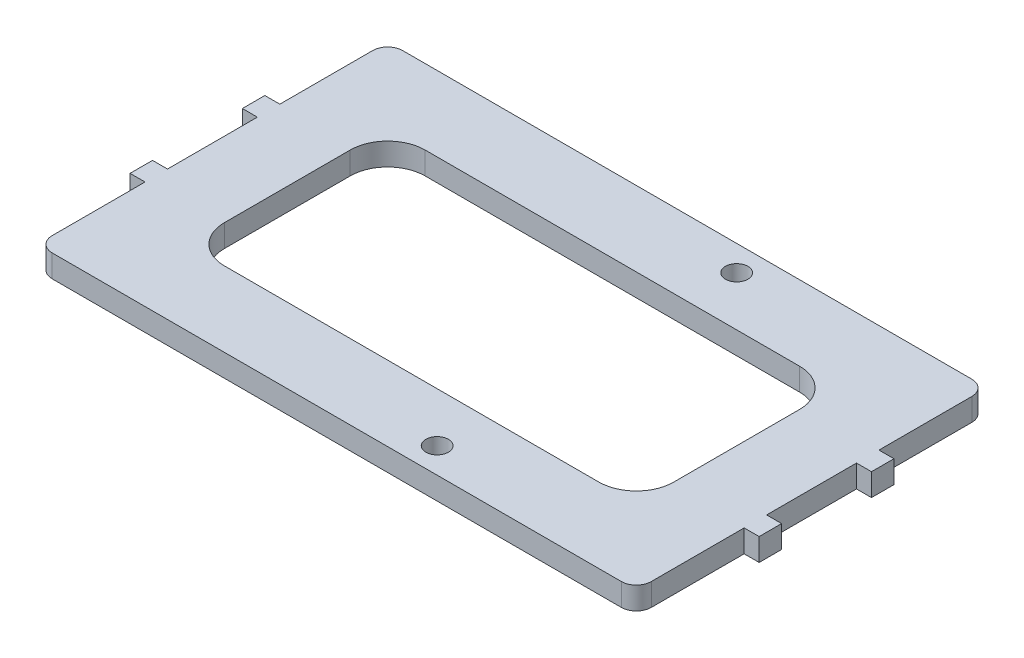
SolidWorks part; units mm, degrees
material "Copper"
ref_plane "Front Plane" through (0, 0, 0) normal (0, 0, 1) x (1, 0, 0)
ref_plane "Top Plane" through (0, 0, 0) normal (0, 1, 0) x (1, 0, 0)
ref_plane "Right Plane" through (0, 0, 0) normal (1, 0, 0) x (0, 0, -1)
sketch "Sketch1" plane through (0, 0, 0) normal (0, 1, 0) x (1, 0, 0)
  line L1 (0, 0) -> (101.6, 0)
  line L2 (0, 0) -> (0, 59.436)
  line L3 (0, 59.436) -> (101.6, 59.436)
  line L4 (101.6, 0) -> (101.6, 59.436)
  dimension "D1" = 59.436
  dimension "D2" = 101.6
extrude "Base Extrude" add sketch "Sketch1" along normal blind 3.81
fillet "Base Corner Fillet" radius 2.54 4 edges at (0, 1.905, 0) (0, 1.905, -59.436) (101.6, 1.905, -59.436) (101.6, 1.905, 0)
sketch "Sketch3" plane through (0, 0, 0) normal (-1, 0, 0) x (0, 0, 1)
  line L0 (-29.718, 3.81) -> (-29.718, 0) construction
  line L1 (-56.896, 3.81) -> (-2.54, 3.81) construction
  line L2 (-56.896, 0) -> (-2.54, 0) construction
  line L3 (-18.288, 3.81) -> (-22.098, 0) construction
  line L4 (-18.288, 0) -> (-22.098, 3.81) construction
  line L5 (-22.098, 0) -> (-22.098, 3.81)
  line L6 (-18.288, 3.81) -> (-22.098, 3.81)
  line L7 (-41.148, 0) -> (-37.338, 0)
  line L8 (-41.148, 0) -> (-41.148, 3.81)
  line L9 (-41.148, 3.81) -> (-37.338, 3.81)
  line L10 (-37.338, 0) -> (-37.338, 3.81)
  line L11 (-41.148, 0) -> (-37.338, 3.81) construction
  line L12 (-41.148, 3.81) -> (-37.338, 0) construction
  line L13 (-18.288, 0) -> (-18.288, 3.81)
  line L14 (-18.288, 0) -> (-22.098, 0)
  dimension "D3" = 3.81
  dimension "D4" = 7.62
extrude "Peg Extrude" add sketch "Sketch3" along normal blind 2.54
ref_plane "Peg Mirror Plane" through (50.8, 0, 0) normal (1, 0, 0) x (0, 0, -1)
mirror "Peg Mirror" about plane through (50.8, 0, 0) normal (1, 0, 0) of "Peg Extrude"
sketch "Sketch4" plane through (0, 0, 0) normal (0, -1, 0) x (1, 0, 0)
  line L0 (2.54, 0) -> (99.06, 0) construction
  line L1 (19.05, -12.7) -> (82.55, -12.7)
  line L2 (12.7, -19.05) -> (12.7, -40.386)
  line L3 (19.05, -46.736) -> (82.55, -46.736)
  line L4 (88.9, -19.05) -> (88.9, -40.386)
  line L5 (99.06, -59.436) -> (2.54, -59.436) construction
  line L8 (0, -37.338) -> (0, -22.098) construction
  line L9 (101.6, -22.098) -> (101.6, -37.338) construction
  arc A0 (82.55, -12.7) -> (88.9, -19.05) centre (82.55, -19.05) cw
  arc A1 (82.55, -46.736) -> (88.9, -40.386) centre (82.55, -40.386) ccw
  arc A2 (12.7, -40.386) -> (19.05, -46.736) centre (19.05, -40.386) ccw
  arc A3 (19.05, -12.7) -> (12.7, -19.05) centre (19.05, -19.05) ccw
  dimension "D5" = 6.35
  dimension "D1" = 12.7
  dimension "D2" = 12.7
  dimension "D3" = 12.7
  dimension "D4" = 12.7
extrude "Material Removal Cut" cut sketch "Sketch4" against normal through all
sketch "Sketch5" plane through (0, 3.81, 0) normal (0, 1, 0) x (1, 0, 0)
  line L0 (0, 29.718) -> (101.6, 29.718) construction
  line L1 (0, 89.154) -> (0, -29.718) construction
  line L2 (101.6, -29.718) -> (101.6, 89.154) construction
  line L3 (63.5, 55.118) -> (63.5, 4.318) construction
  circle A0 centre (63.5, 4.318) radius 1.905
  circle A1 centre (63.5, 55.118) radius 1.905
  point P4 (63.5, 29.718)
  dimension "D1" = 3.81
  dimension "D2" = 50.8
  dimension "D3" = 63.5
extrude "Remote Control Holder Cut" cut sketch "Sketch5" against normal through all
